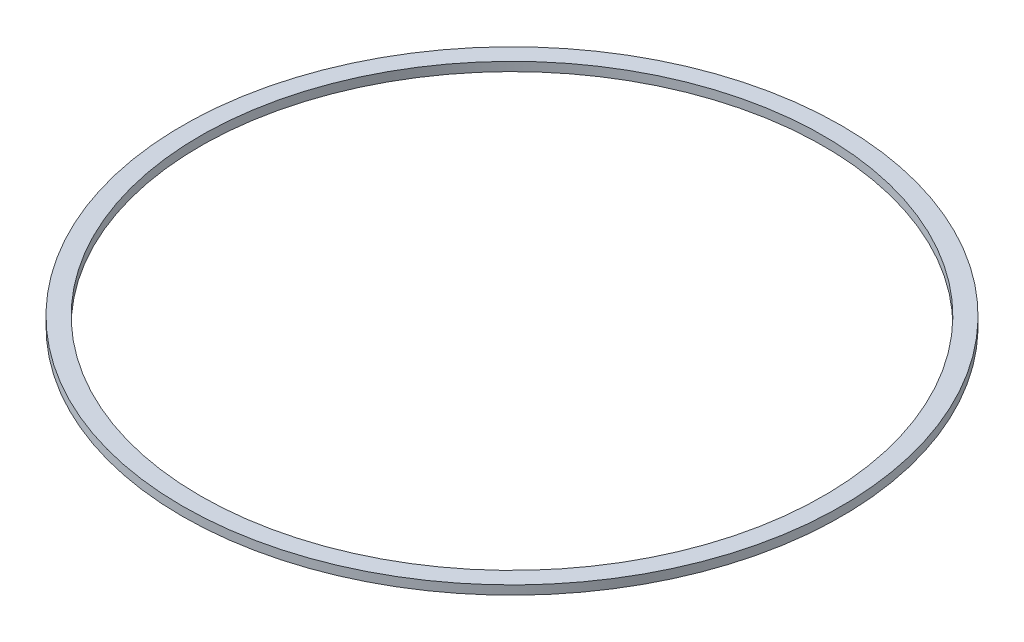
SolidWorks part; units mm, degrees
ref_plane "Front Plane" through (0, 0, 0) normal (0, 0, 1) x (1, 0, 0)
ref_plane "Top Plane" through (0, 0, 0) normal (0, 1, 0) x (1, 0, 0)
ref_plane "Right Plane" through (0, 0, 0) normal (1, 0, 0) x (0, 0, -1)
sketch "Sketch1" plane through (0, 0, 0) normal (0, 1, 0) x (1, 0, 0)
  circle A0 centre (0, 0) radius 35
  circle A1 centre (0, 0) radius 37
  dimension "D1" = 70
  dimension "D2" = 2
extrude "Boss-Extrude1" add sketch "Sketch1" along normal blind 1
